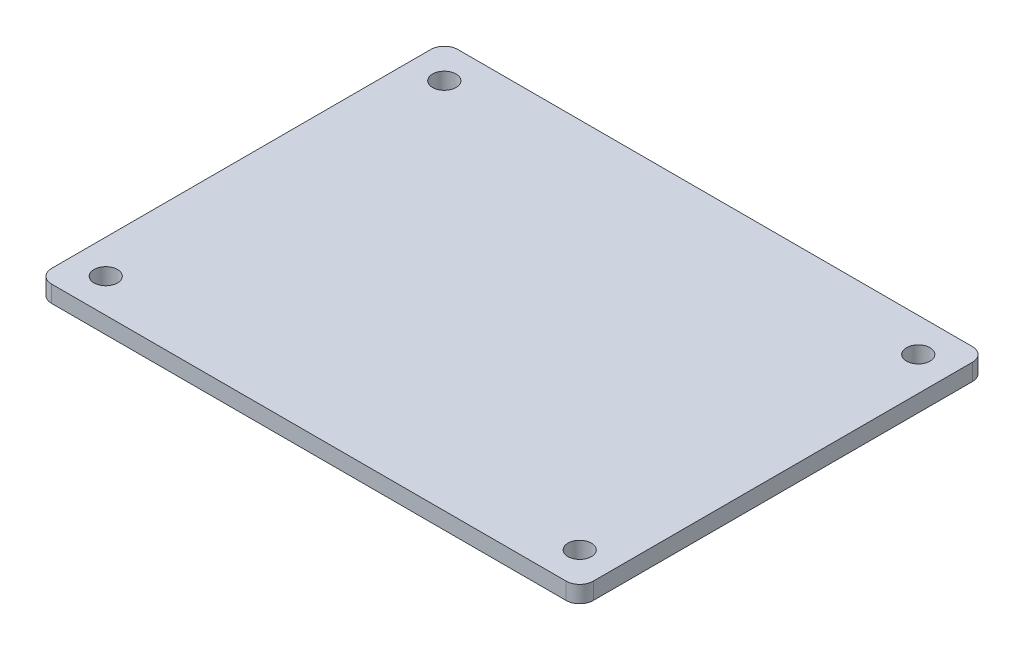
SolidWorks part; units mm, degrees
ref_plane "Front Plane" through (0, 0, 0) normal (0, 0, 1) x (1, 0, 0)
ref_plane "Top Plane" through (0, 0, 0) normal (0, 1, 0) x (1, 0, 0)
ref_plane "Right Plane" through (0, 0, 0) normal (1, 0, 0) x (0, 0, -1)
sketch "Sketch1" plane through (0, 0, 0) normal (0, 1, 0) x (1, 0, 0)
  line L1 (-25.4, 19.05) -> (25.4, 19.05)
  line L2 (-25.4, 19.05) -> (-25.4, -19.05)
  line L3 (-25.4, -19.05) -> (25.4, -19.05)
  line L4 (25.4, 19.05) -> (25.4, -19.05)
  line L5 (-25.4, 19.05) -> (25.4, -19.05) construction
  line L6 (-25.4, -19.05) -> (25.4, 19.05) construction
  line L7 (-22.225, 15.875) -> (22.225, 15.875)
  line L8 (-22.225, 15.875) -> (-22.225, -15.875)
  line L9 (-22.225, -15.875) -> (22.225, -15.875)
  line L10 (22.225, 15.875) -> (22.225, -15.875)
  line L11 (-22.225, 15.875) -> (22.225, -15.875) construction
  line L12 (-22.225, -15.875) -> (22.225, 15.875) construction
  circle A0 centre (22.225, 15.875) radius 1.1
  circle A1 centre (22.225, -15.875) radius 1.1
  circle A2 centre (-22.225, -15.875) radius 1.1
  circle A3 centre (-22.225, 15.875) radius 1.1
  point P0 (0, 0)
  point P6 (0, 0)
  dimension "D5" = 2.2
  dimension "D1" = 50.8
  dimension "D2" = 38.1
  dimension "D3" = 44.45
  dimension "D4" = 31.75
extrude "Boss-Extrude1" add sketch "Sketch1" along normal blind 1.5748 contours L4 L1 L2 L3 A3 L7 A0 L10 A1 L9 A2 L8 | A3 L8 A2 L9 A1 L10 A0 L7
fillet "Fillet1" radius 1.27 4 edges at (-25.4, 0.7874, -19.05) (25.4, 0.7874, -19.05) (-25.4, 0.7874, 19.05) (25.4, 0.7874, 19.05)
